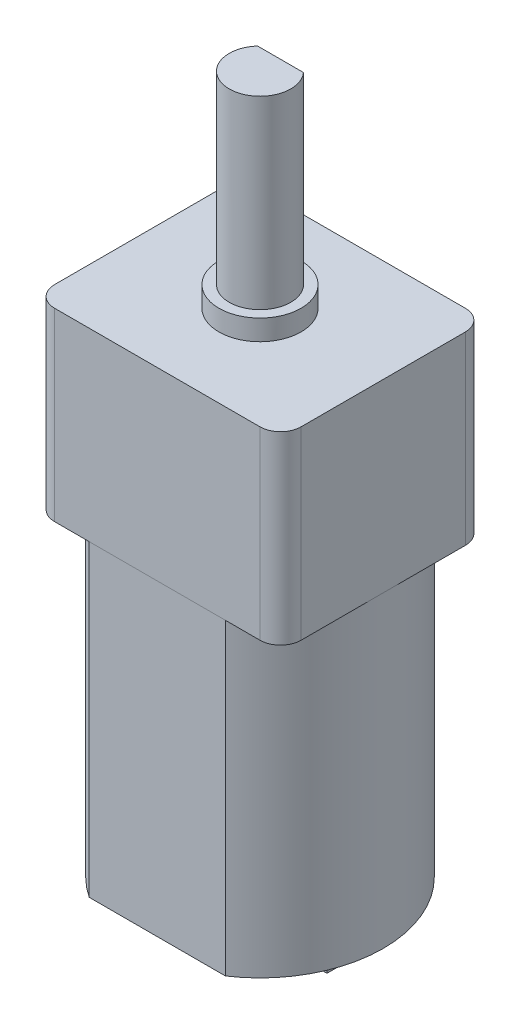
SolidWorks part; units mm, degrees
ref_plane "Front Plane" through (0, 0, 0) normal (0, 0, 1) x (1, 0, 0)
ref_plane "Top Plane" through (0, 0, 0) normal (0, 1, 0) x (1, 0, 0)
ref_plane "Right Plane" through (0, 0, 0) normal (1, 0, 0) x (0, 0, -1)
sketch "Sketch1" plane through (0, 0, 0) normal (0, 1, 0) x (1, 0, 0)
  line L0 (0, 0) -> (7.5343, 0) construction
  line L1 (-3.3166, 5) -> (3.3166, 5)
  line L2 (-3.3166, -5) -> (3.3166, -5)
  arc A0 (-3.3166, 5) -> (-3.3166, -5) centre (0, 0) ccw
  arc A1 (3.3166, -5) -> (3.3166, 5) centre (0, 0) ccw
  dimension "D1" = 5
extrude "Boss-Extrude1" add sketch "Sketch1" along normal blind 15
sketch "Sketch2" plane through (0, 0, 0) normal (0, -1, 0) x (-1, 0, 0)
  line L0 (0, 0) -> (-4.2986, 0) construction
  line L1 (0, 0) -> (0, -3.5995) construction
  line L2 (4.177, -0.9154) -> (3.9877, -0.9154)
  line L3 (4.177, -0.9154) -> (4.177, 0.9154)
  line L4 (4.177, 0.9154) -> (3.9877, 0.9154)
  line L5 (3.9877, -0.9154) -> (3.9877, 0.9154)
  line L6 (4.177, -0.9154) -> (3.9877, 0.9154) construction
  line L7 (4.177, 0.9154) -> (3.9877, -0.9154) construction
  line L8 (-4.177, 0.9154) -> (-3.9877, -0.9154) construction
  line L9 (-4.177, -0.9154) -> (-3.9877, 0.9154) construction
  line L10 (-3.9877, -0.9154) -> (-3.9877, 0.9154)
  line L11 (-4.177, 0.9154) -> (-3.9877, 0.9154)
  line L12 (-4.177, -0.9154) -> (-4.177, 0.9154)
  line L13 (-4.177, -0.9154) -> (-3.9877, -0.9154)
  circle A0 centre (0, 0) radius 2.5
  point P3 (4.0824, 0)
  point P16 (-4.0824, 0)
extrude "Boss-Extrude2" add sketch "Sketch2" along normal blind 1.5
sketch "Sketch3" plane through (0, 15, 0) normal (0, 1, 0) x (1, 0, 0)
  line L0 (-3.3166, -5) -> (3.3166, -5) construction
  line L1 (5, 5) -> (-5, 5)
  line L2 (6, 4) -> (6, -4)
  line L3 (5, -5) -> (-5, -5)
  line L4 (-6, 4) -> (-6, -4)
  line L5 (6, 5) -> (-6, -5) construction
  line L6 (6, -5) -> (-6, 5) construction
  arc A0 (-5, -5) -> (-6, -4) centre (-5, -4) cw
  arc A1 (-6, 4) -> (-5, 5) centre (-5, 4) cw
  arc A2 (5, 5) -> (6, 4) centre (5, 4) cw
  arc A3 (6, -4) -> (5, -5) centre (5, -4) cw
  point P0 (0, 0)
  dimension "D1" = 1
extrude "Boss-Extrude3" add sketch "Sketch3" along normal blind 9 separate body
sketch "Sketch4" plane through (0, 24, 0) normal (0, 1, 0) x (1, 0, 0)
  circle A0 centre (0, 0) radius 2
extrude "Boss-Extrude4" add sketch "Sketch4" along normal blind 1
sketch "Sketch5" plane through (0, 24, 0) normal (0, 1, 0) x (1, 0, 0)
  circle A0 centre (0, 0) radius 1.5
extrude "Boss-Extrude5" add sketch "Sketch5" along normal blind 10
sketch "Sketch6" plane through (0, 34, 0) normal (0, 1, 0) x (1, 0, 0)
  line L0 (-1.118, 1) -> (1.118, 1)
  circle A2 centre (0, 0) radius 1.5 construction
  arc A3 (-1.118, 1) -> (1.118, 1) centre (0, 0) cw
  dimension "D1" = 1
extrude "Cut-Extrude1" cut sketch "Sketch6" against normal blind 8.5
